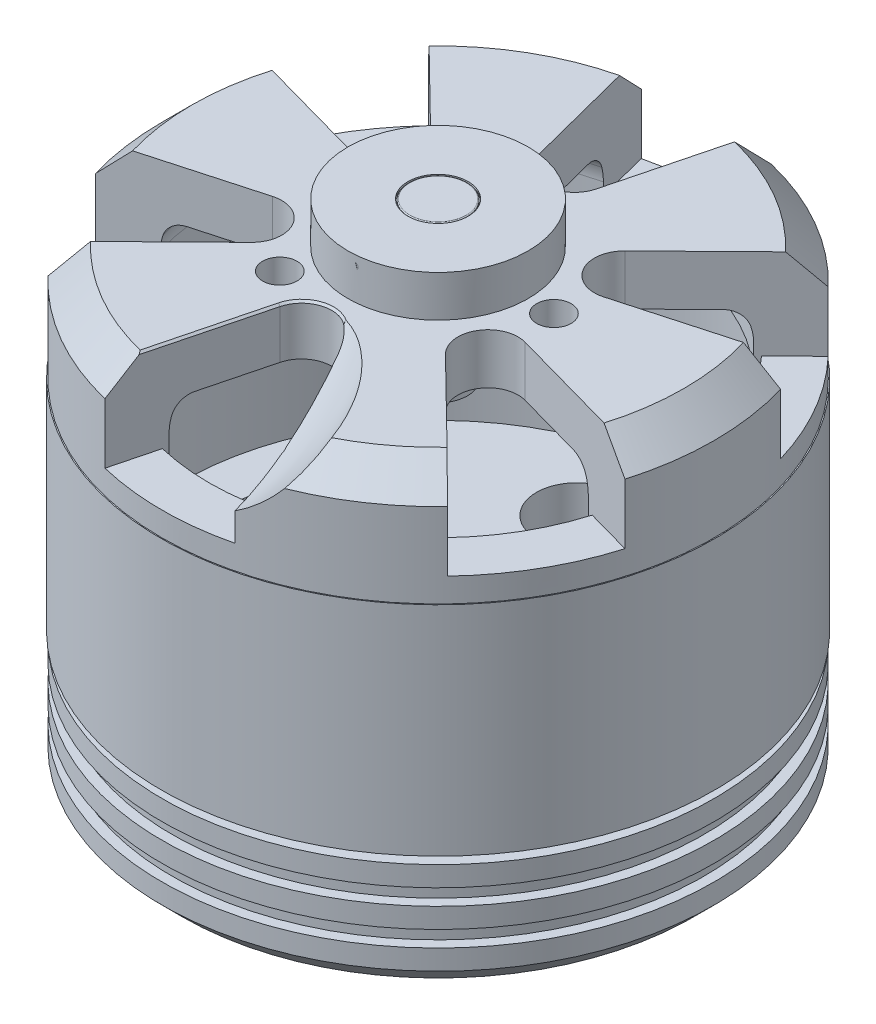
SolidWorks part; units mm, degrees
ref_plane "Front Plane" through (0, 0, 0) normal (0, 0, 1) x (1, 0, 0)
ref_plane "Top Plane" through (0, 0, 0) normal (0, 1, 0) x (1, 0, 0)
ref_plane "Right Plane" through (0, 0, 0) normal (1, 0, 0) x (0, 0, -1)
sketch "Sketch1" plane through (0, 0, 0) normal (1, 0, 0) x (0, 0, -1)
  line L0 (0, 0) -> (0, 92.5162) construction
  line L1 (0, 0) -> (12.75, 0)
  line L2 (13.75, 1) -> (13.75, 2)
  line L3 (13.75, 2) -> (13.25, 2)
  line L4 (13.25, 2) -> (13.25, 2.8)
  line L5 (13.25, 2.8) -> (13.75, 2.8)
  line L6 (13.75, 2.8) -> (13.75, 3.8)
  line L7 (13.75, 3.8) -> (13.25, 3.8)
  line L8 (13.25, 3.8) -> (13.25, 4.6)
  line L9 (13.25, 4.6) -> (13.75, 4.6)
  line L10 (13.75, 4.6) -> (13.75, 5.6)
  line L11 (13.75, 5.6) -> (0, 5.6)
  line L12 (12.75, 0) -> (13.75, 1)
  line L13 (0, 0) -> (0, 5.6)
  point P4 (13.75, 0)
  dimension "D1" = 27.5
  dimension "D2" = 2
  dimension "D3" = 1
  dimension "D4" = 0.8
  dimension "D5" = 1
  dimension "D6" = 26.5
revolve "Revolve1" add sketch "Sketch1" angle 360 about L0
ref_plane "Plane1" through (0, 6, 0) normal (0, -1, 0) x (1, 0, 0)
sketch "Sketch2" plane through (0, 6, 0) normal (0, -1, 0) x (1, 0, 0)
  circle A0 centre (0, 0) radius 13.8
  circle A1 centre (0, 0) radius 12.8
  dimension "D1" = 27.6
  dimension "D2" = 1
extrude "Steel" add sketch "Sketch2" against normal blind 10.85 separate body
sketch "Sketch3" plane through (0, 16.85, 0) normal (0, 1, 0) x (1, 0, 0)
  circle A0 centre (0, 0) radius 13.75
  dimension "D1" = 27.5
extrude "Boss-Extrude2" add sketch "Sketch3" along normal offset from surface (5.7 mm away) 22.55 separate body up to face at (0, 0, -12.75)
sketch "Sketch5" plane through (0, 22.55, 0) normal (0, 1, 0) x (1, 0, 0)
  circle A0 centre (0, 0) radius 4.49
  dimension "D1" = 8.98
extrude "Boss-Extrude3" add sketch "Sketch5" along normal blind 2.06
chamfer "Chamfer1" distance 1.5 angle 45 1 edges at (0, 22.55, -13.75)
sketch "Sketch6" plane through (0, 22.55, 0) normal (0, 1, 0) x (1, 0, 0)
  line L0 (0, 0) -> (0, 13.8) construction
  line L1 (3.25, 13.4118) -> (1.4527, 6.4262)
  line L2 (-3.25, 13.4118) -> (-1.4527, 6.4262)
  line L3 (13.24, 3.8913) -> (6.2916, 1.9551)
  line L4 (9.99, 9.5205) -> (4.8389, 4.4712)
  line L5 (9.99, -9.5205) -> (4.8389, -4.4712)
  line L6 (13.24, -3.8913) -> (6.2916, -1.9551)
  line L7 (-3.25, -13.4118) -> (-1.4527, -6.4262)
  line L8 (3.25, -13.4118) -> (1.4527, -6.4262)
  line L9 (-13.24, -3.8913) -> (-6.2916, -1.9551)
  line L10 (-9.99, -9.5205) -> (-4.8389, -4.4712)
  line L11 (-9.99, 9.5205) -> (-4.8389, 4.4712)
  line L12 (-13.24, 3.8913) -> (-6.2916, 1.9551)
  circle A0 centre (0, 0) radius 13.8 construction
  circle A1 centre (0, 0) radius 5.3 construction
  arc A2 (-1.4527, 6.4262) -> (1.4527, 6.4262) centre (0, 6.8) ccw
  arc A3 (3.25, 13.4118) -> (-3.25, 13.4118) centre (0, 0) ccw
  arc A4 (4.8389, 4.4712) -> (6.2916, 1.9551) centre (5.889, 3.4) ccw
  arc A5 (13.24, 3.8913) -> (9.99, 9.5205) centre (0, 0) ccw
  arc A6 (6.2916, -1.9551) -> (4.8389, -4.4712) centre (5.889, -3.4) ccw
  arc A7 (9.99, -9.5205) -> (13.24, -3.8913) centre (0, 0) ccw
  arc A8 (1.4527, -6.4262) -> (-1.4527, -6.4262) centre (0, -6.8) ccw
  arc A9 (-3.25, -13.4118) -> (3.25, -13.4118) centre (0, 0) ccw
  arc A10 (-4.8389, -4.4712) -> (-6.2916, -1.9551) centre (-5.889, -3.4) ccw
  arc A11 (-13.24, -3.8913) -> (-9.99, -9.5205) centre (0, 0) ccw
  arc A12 (-6.2916, 1.9551) -> (-4.8389, 4.4712) centre (-5.889, 3.4) ccw
  arc A13 (-9.99, 9.5205) -> (-13.24, 3.8913) centre (0, 0) ccw
  point P12 (0, 5.3)
  point P20 (4.5899, 2.65)
  point P27 (4.5899, -2.65)
  point P34 (0, -5.3)
  point P41 (-4.5899, -2.65)
  point P48 (-4.5899, 2.65)
  dimension "D2" = 10.6
  dimension "D3" = 1.5
  dimension "D1" = 6.5
  dimension "D4" = 6
extrude "Cut-Extrude1" cut sketch "Sketch6" against normal blind 4.5
sketch "Sketch7" plane through (0, 18.05, 0) normal (0, 1, 0) x (1, 0, 0)
  line L0 (8.2759, 7.8403) -> (4.8389, 4.4712)
  line L1 (6.2916, 1.9551) -> (10.9278, 3.247)
  line L2 (-3.2375, 13.3634) -> (-1.4527, 6.4262)
  line L3 (1.4527, 6.4262) -> (3.2375, 13.3634)
  line L4 (-2.6519, 11.0873) -> (-1.4527, 6.4262)
  line L5 (1.4527, 6.4262) -> (2.6519, 11.0873)
  line L6 (10.9278, -3.247) -> (6.2916, -1.9551)
  line L7 (4.8389, -4.4712) -> (8.2759, -7.8403)
  line L8 (2.6519, -11.0873) -> (1.4527, -6.4262)
  line L9 (-1.4527, -6.4262) -> (-2.6519, -11.0873)
  line L10 (-8.2759, -7.8403) -> (-4.8389, -4.4712)
  line L11 (-6.2916, -1.9551) -> (-10.9278, -3.247)
  line L12 (-10.9278, 3.247) -> (-6.2916, 1.9551)
  line L13 (-4.8389, 4.4712) -> (-8.2759, 7.8403)
  arc A0 (2.6519, 11.0873) -> (-2.6519, 11.0873) centre (0, 0) ccw
  arc A1 (10.9278, 3.247) -> (8.2759, 7.8403) centre (0, 0) ccw
  arc A2 (3.2375, 13.3634) -> (-3.2375, 13.3634) centre (0, 0) ccw
  arc A3 (-1.4527, 6.4262) -> (1.4527, 6.4262) centre (0, 6.8) ccw
  arc A4 (3.2375, 13.3634) -> (-3.2375, 13.3634) centre (0, 0) ccw construction
  arc A5 (-1.4527, 6.4262) -> (1.4527, 6.4262) centre (0, 6.8) ccw
  arc A7 (4.8389, 4.4712) -> (6.2916, 1.9551) centre (5.889, 3.4) ccw
  arc A8 (8.2759, -7.8403) -> (10.9278, -3.247) centre (0, 0) ccw
  arc A10 (6.2916, -1.9551) -> (4.8389, -4.4712) centre (5.889, -3.4) ccw
  arc A11 (-2.6519, -11.0873) -> (2.6519, -11.0873) centre (0, 0) ccw
  arc A13 (1.4527, -6.4262) -> (-1.4527, -6.4262) centre (0, -6.8) ccw
  arc A14 (-10.9278, -3.247) -> (-8.2759, -7.8403) centre (0, 0) ccw
  arc A16 (-4.8389, -4.4712) -> (-6.2916, -1.9551) centre (-5.889, -3.4) ccw
  arc A17 (-8.2759, 7.8403) -> (-10.9278, 3.247) centre (0, 0) ccw
  arc A19 (-6.2916, 1.9551) -> (-4.8389, 4.4712) centre (-5.889, 3.4) ccw
  arc A20 (-9.9543, 9.4855) -> (-13.1918, 3.8779) centre (0, 0) ccw [skipped]
  arc A21 (-13.1918, -3.8779) -> (-9.9543, -9.4855) centre (0, 0) ccw [skipped]
  arc A22 (-3.2375, -13.3634) -> (3.2375, -13.3634) centre (0, 0) ccw [skipped]
  arc A23 (9.9543, -9.4855) -> (13.1918, -3.8779) centre (0, 0) ccw [skipped]
  arc A24 (13.1918, 3.8779) -> (9.9543, 9.4855) centre (0, 0) ccw [skipped]
  dimension "D2" = 2.35
  dimension "D1" = 0
  dimension "D3" = 6
extrude "Cut-Extrude2" cut sketch "Sketch7" against normal blind 4.5
ref_plane "Plane2" through (0, 11.275, -11.275) normal (0, -0.7071, 0.7071) x (1, 0, 0)
ref_plane "Plane3" through (0, 22.5887, -22.5887) normal (0, -0.7071, 0.7071) x (1, 0, 0)
ref_plane "Plane4" through (0, 25.55, 0) normal (0, 1, 0) x (-1, 0, 0)
sketch "Sketch8" plane through (0, 0, 0) normal (1, 0, 0) x (0, 0, -1)
  line L0 (0, 0) -> (0, 24.61) construction
  line L1 (-12.75, 0) -> (12.75, 0) construction
  line L2 (4.49, 24.61) -> (-4.49, 24.61) construction
  line L3 (11.1251, 16.85) -> (11.1251, 18.644)
  line L4 (11.0873, 16.85) -> (11.4, 16.85) construction
  line L5 (10.0653, 20.0415) -> (1.473, 20.0415)
  line L6 (1.473, 20.0415) -> (1.473, 16.85)
  line L7 (-13.75, 16.85) -> (13.75, 16.85) construction
  line L8 (1.473, 16.85) -> (11.1251, 16.85)
  arc A0 (11.1251, 18.644) -> (11.0211, 19.3357) centre (8.7737, 18.644) ccw
  arc A1 (11.0211, 19.3357) -> (10.0653, 20.0415) centre (10.0653, 19.0415) ccw
  dimension "D1" = 1
revolve "Cut-Revolve1" cut sketch "Sketch8" angle 360 about L0
chamfer "Chamfer7" distance 0.1 angle 45 3 edges at (-2.1582, 22.55, 9.1684) (0, 22.55, 5.3) (2.1582, 22.55, 9.1684)
sketch "Sketch10" plane through (0, 25.55, 0) normal (0, 1, 0) x (1, 0, 0)
  line L0 (0, 0) -> (0, -13.75) construction
  line L4 (0, -14.8583) -> (3.0856, -19.4184)
  line L5 (0, -5.9642) -> (0, -14.8583)
  line L6 (3.0856, -19.4184) -> (6.957, -13.75)
  arc A0 (-3.2375, -13.3634) -> (3.2375, -13.3634) centre (0, 0) ccw construction
  arc A4 (0, -5.9642) -> (2.5253, -4.8694) centre (1.5, -5.9642) cw
  arc A5 (2.5253, -4.8694) -> (6.957, -13.75) centre (-7.226, -15.2817) cw
  point P7 (0, -2.9817)
  dimension "D1" = 1.5
revolve "Cut-Revolve2" cut sketch "Sketch10" angle 74 about L0
sketch "Sketch11" plane through (0, 22.55, 0) normal (0, 1, 0) x (1, 0, 0)
  line L1 (5.7735, 0) -> (-2.8868, 5) construction
  line L2 (-2.8868, 5) -> (-2.8868, -5) construction
  line L3 (-2.8868, -5) -> (5.7735, 0) construction
  circle A0 centre (0, 0) radius 2.8868 construction
  circle A1 centre (-2.8868, 5) radius 0.8586
  circle A2 centre (5.7735, 0) radius 0.8586
  circle A3 centre (-2.8868, -5) radius 0.8586
  dimension "D1" = 10
extrude "Cut-Extrude4" cut sketch "Sketch11" against normal blind 13.5
sketch "Sketch12" plane through (0, 24.61, 0) normal (0, 1, 0) x (1, 0, 0)
  circle A0 centre (0, 0) radius 1.5
  dimension "D1" = 3
extrude "Cut-Extrude5" cut sketch "Sketch12" against normal blind 0.1
sketch "Sketch13" plane through (0, 24.51, 0) normal (0, 1, 0) x (1, 0, 0)
  circle A2 centre (0, 0) radius 1.45
  circle A3 centre (0, 0) radius 1.45
  dimension "D1" = 0.05
extrude "Boss-Extrude4" add sketch "Sketch13" along normal blind 0.1 separate body
fillet "Fillet1" radius 0.05 1 edges at (0, 24.61, 1.45)
sketch "Sketch14" plane through (0, 0, 0) normal (0, -1, 0) x (1, 0, 0)
  line L0 (0, 0) -> (0, 13.8) construction
  circle A0 centre (0, 0) radius 13.8 construction
  arc A1 (-1.8948, 8.7983) -> (1.8948, 8.7983) centre (0, 0) cw construction
  arc A2 (2.3159, 10.7534) -> (-2.3159, 10.7534) centre (0, 0) ccw
  arc A3 (1.4738, 6.8431) -> (-1.4738, 6.8431) centre (0, 0) ccw
  arc A4 (1.4738, 6.8431) -> (2.3159, 10.7534) centre (1.8948, 8.7983) ccw
  arc A5 (-2.3159, 10.7534) -> (-1.4738, 6.8431) centre (-1.8948, 8.7983) ccw
  arc A6 (8.7983, 1.8948) -> (8.7983, -1.8948) centre (0, 0) cw construction
  arc A7 (10.7534, -2.3159) -> (10.7534, 2.3159) centre (0, 0) ccw
  arc A8 (6.8431, -1.4738) -> (6.8431, 1.4738) centre (0, 0) ccw
  arc A9 (6.8431, -1.4738) -> (10.7534, -2.3159) centre (8.7983, -1.8948) ccw
  arc A10 (10.7534, 2.3159) -> (6.8431, 1.4738) centre (8.7983, 1.8948) ccw
  arc A11 (1.8948, -8.7983) -> (-1.8948, -8.7983) centre (0, 0) cw construction
  arc A12 (-2.3159, -10.7534) -> (2.3159, -10.7534) centre (0, 0) ccw
  arc A13 (-1.4738, -6.8431) -> (1.4738, -6.8431) centre (0, 0) ccw
  arc A14 (-1.4738, -6.8431) -> (-2.3159, -10.7534) centre (-1.8948, -8.7983) ccw
  arc A15 (2.3159, -10.7534) -> (1.4738, -6.8431) centre (1.8948, -8.7983) ccw
  arc A16 (-8.7983, -1.8948) -> (-8.7983, 1.8948) centre (0, 0) cw construction
  arc A17 (-10.7534, 2.3159) -> (-10.7534, -2.3159) centre (0, 0) ccw
  arc A18 (-6.8431, 1.4738) -> (-6.8431, -1.4738) centre (0, 0) ccw
  arc A19 (-6.8431, 1.4738) -> (-10.7534, 2.3159) centre (-8.7983, 1.8948) ccw
  arc A20 (-10.7534, -2.3159) -> (-6.8431, -1.4738) centre (-8.7983, -1.8948) ccw
  point P9 (0, 9)
  point P14 (-3.85, 8.3772)
  point P15 (3.85, 8.3772)
  point P22 (9, 0)
  point P27 (8.3772, 3.85)
  point P28 (8.3772, -3.85)
  point P32 (0, -9)
  point P37 (3.85, -8.3772)
  point P38 (-3.85, -8.3772)
  point P42 (-9, 0)
  point P47 (-8.3772, -3.85)
  point P48 (-8.3772, 3.85)
  dimension "D1" = 4
  dimension "D2" = 7.7
  dimension "D3" = 9
  dimension "D4" = 4
extrude "Cut-Extrude6" cut sketch "Sketch14" against normal blind 10
sketch "Sketch15" plane through (0, 0, 0) normal (0, -1, 0) x (1, 0, 0)
  line L0 (0, 0) -> (0, 13.8) construction
  line L1 (0, 0) -> (9.7581, 9.7581) construction
  line L2 (0, 0) -> (13.75, 0) construction
  line L3 (0, 0) -> (-9.7227, 9.7227) construction
  circle A0 centre (0, 0) radius 13.8 construction
  circle A1 centre (6.7175, 6.7175) radius 1.2
  circle A2 centre (0, 0) radius 13.75 construction
  circle A3 centre (-6.7175, -6.7175) radius 1.2
  circle A4 centre (-5.6569, 5.6569) radius 1.2
  circle A5 centre (5.6569, -5.6569) radius 1.2
  dimension "D2" = 2.4
  dimension "D1" = 45
  dimension "D3" = 45
  dimension "D4" = 90
  dimension "D5" = 19
  dimension "D6" = 16
extrude "Cut-Extrude7" cut sketch "Sketch15" against normal blind 5
sketch "Sketch16" plane through (0, 0, 0) normal (0, -1, 0) x (1, 0, 0)
  circle A0 centre (0, 0) radius 2.8
  dimension "D1" = 5.6
extrude "Boss-Extrude5" add sketch "Sketch16" along normal blind 1.3 separate body
sketch "Sketch17" plane through (0, -1.3, 0) normal (0, -1, 0) x (1, 0, 0)
  circle A0 centre (0, 0) radius 1.475
  dimension "D1" = 2.95
extrude "Boss-Extrude6" add sketch "Sketch17" along normal blind 0.95 separate body
fillet "Fillet2" radius 0.1 1 edges at (0, -2.25, -1.475)
